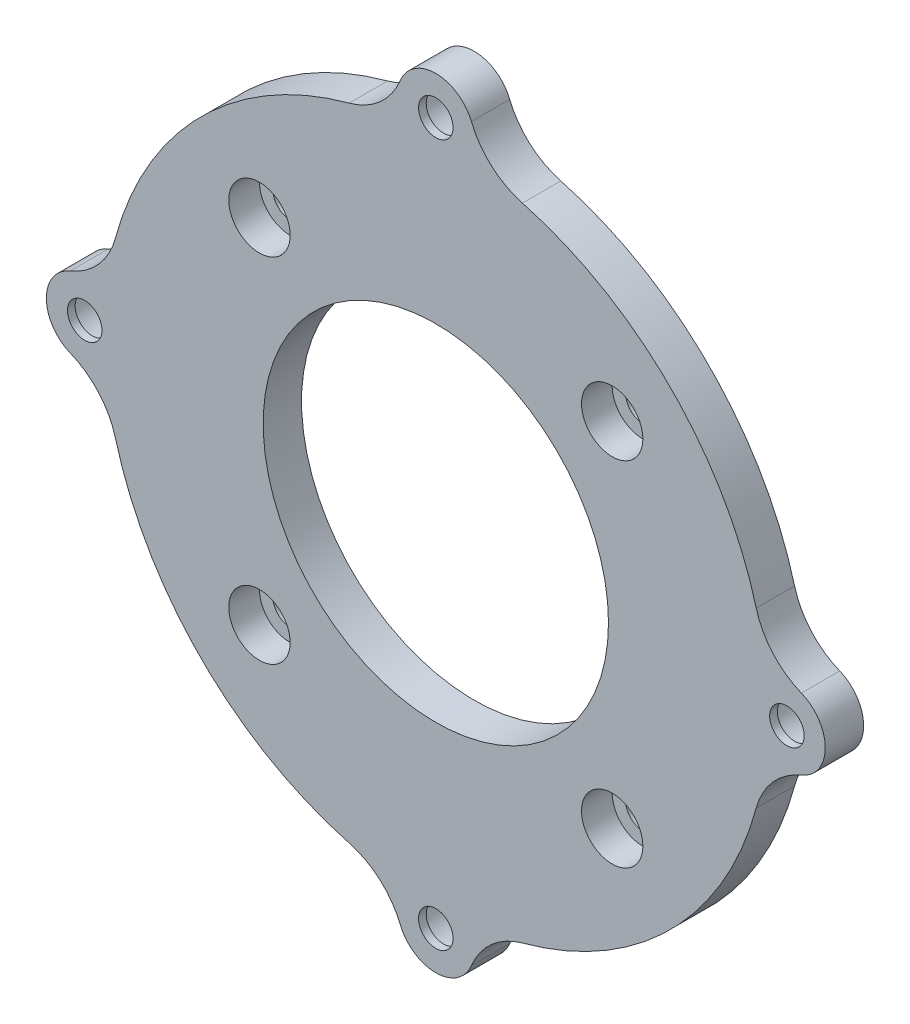
SolidWorks part; units mm, degrees
material "6061-T6 (SS)"
ref_plane "Front Plane" through (0, 0, 0) normal (0, 0, 1) x (1, 0, 0)
ref_plane "Top Plane" through (0, 0, 0) normal (0, 1, 0) x (1, 0, 0)
ref_plane "Right Plane" through (0, 0, 0) normal (1, 0, 0) x (0, 0, -1)
sketch "Sketch1" plane through (0, 0, 0) normal (0, 0, 1) x (1, 0, 0)
  line L0 (0, 0) -> (-22.981, 22.981) construction
  line L1 (0, 0) -> (-30.5824, 30.5824) construction
  line L2 (-30.5824, 30.5824) -> (30.5824, 30.5824) construction
  line L3 (30.5824, 30.5824) -> (0, 0) construction
  circle A0 centre (0, 0) radius 45.75 construction
  circle A1 centre (0, 0) radius 32.5 construction
  circle A3 centre (-45.75, 0) radius 2.25
  circle A4 centre (0, 0) radius 32.5 construction
  circle A5 centre (0, 45.75) radius 2.25
  circle A6 centre (0, 0) radius 32.5 construction
  circle A7 centre (45.75, 0) radius 2.25
  circle A8 centre (0, 0) radius 32.5 construction
  circle A9 centre (0, -45.75) radius 2.25
  circle A10 centre (-22.981, 22.981) radius 2.25
  circle A11 centre (22.981, 22.981) radius 2.25
  circle A12 centre (22.981, -22.981) radius 2.25
  circle A13 centre (-22.981, -22.981) radius 2.25
  circle A14 centre (0, 0) radius 22.5
  arc A16 (4.631, 47.6352) -> (-4.631, 47.6352) centre (0, 45.75) ccw
  arc A17 (-4.631, 47.6352) -> (-11.2839, 41.7521) centre (-13.8929, 51.4057) cw
  arc A18 (4.631, 47.6352) -> (11.2839, 41.7521) centre (13.8929, 51.4057) ccw
  arc A19 (-41.7521, -11.2839) -> (-11.2839, -41.7521) centre (0, 0) ccw
  arc A20 (47.6352, 4.631) -> (41.7521, 11.2839) centre (51.4057, 13.8929) cw
  arc A21 (47.6352, -4.631) -> (47.6352, 4.631) centre (45.75, 0) ccw
  arc A22 (47.6352, -4.631) -> (41.7521, -11.2839) centre (51.4057, -13.8929) ccw
  arc A23 (4.631, -47.6352) -> (11.2839, -41.7521) centre (13.8929, -51.4057) cw
  arc A24 (-4.631, -47.6352) -> (4.631, -47.6352) centre (0, -45.75) ccw
  arc A25 (-4.631, -47.6352) -> (-11.2839, -41.7521) centre (-13.8929, -51.4057) ccw
  arc A26 (-47.6352, -4.631) -> (-41.7521, -11.2839) centre (-51.4057, -13.8929) cw
  arc A27 (-47.6352, 4.631) -> (-47.6352, -4.631) centre (-45.75, 0) ccw
  arc A28 (-47.6352, 4.631) -> (-41.7521, 11.2839) centre (-51.4057, 13.8929) ccw
  arc A29 (-11.2839, 41.7521) -> (-41.7521, 11.2839) centre (0, 0) ccw
  arc A30 (41.7521, 11.2839) -> (11.2839, 41.7521) centre (0, 0) ccw
  arc A31 (11.2839, -41.7521) -> (41.7521, -11.2839) centre (0, 0) ccw
  point P19 (0, 0)
  point P28 (0, 0)
  point P58 (0, 0)
  dimension "D1" = 4.5
  dimension "D3" = 4.5
  dimension "D5" = 45
  dimension "D6" = 10
  dimension "D7" = 91.5
  dimension "D8" = 65
  dimension "D11" = 10
  dimension "D12" = 10
  dimension "D9" = 0
  dimension "D13" = 90
  dimension "D2" = 4
  dimension "D4" = 4
  dimension "D14" = 4
extrude "Boss-Extrude1" add sketch "Sketch1" along normal mid plane 5
sketch "Sketch3" plane through (0, 0, 2.5) normal (0, 0, 1) x (1, 0, 0)
  circle A3 centre (-22.981, -22.981) radius 4
  circle A6 centre (-22.981, 22.981) radius 4
  circle A9 centre (22.981, 22.981) radius 4
  circle A12 centre (22.981, -22.981) radius 4
  point P15 (0, 0)
  dimension "D1" = 8
extrude "Cut-Extrude2" cut sketch "Sketch3" against normal blind 4
sketch "Sketch4" plane through (0, 0, -2.5) normal (0, 0, -1) x (-1, 0, 0)
  circle A2 centre (0, 45.75) radius 4
  circle A4 centre (45.75, 0) radius 4
  circle A6 centre (0, -45.75) radius 4
  circle A8 centre (-45.75, 0) radius 4
  point P13 (0, 0)
  dimension "D1" = 8
extrude "Cut-Extrude3" cut sketch "Sketch4" against normal blind 4
